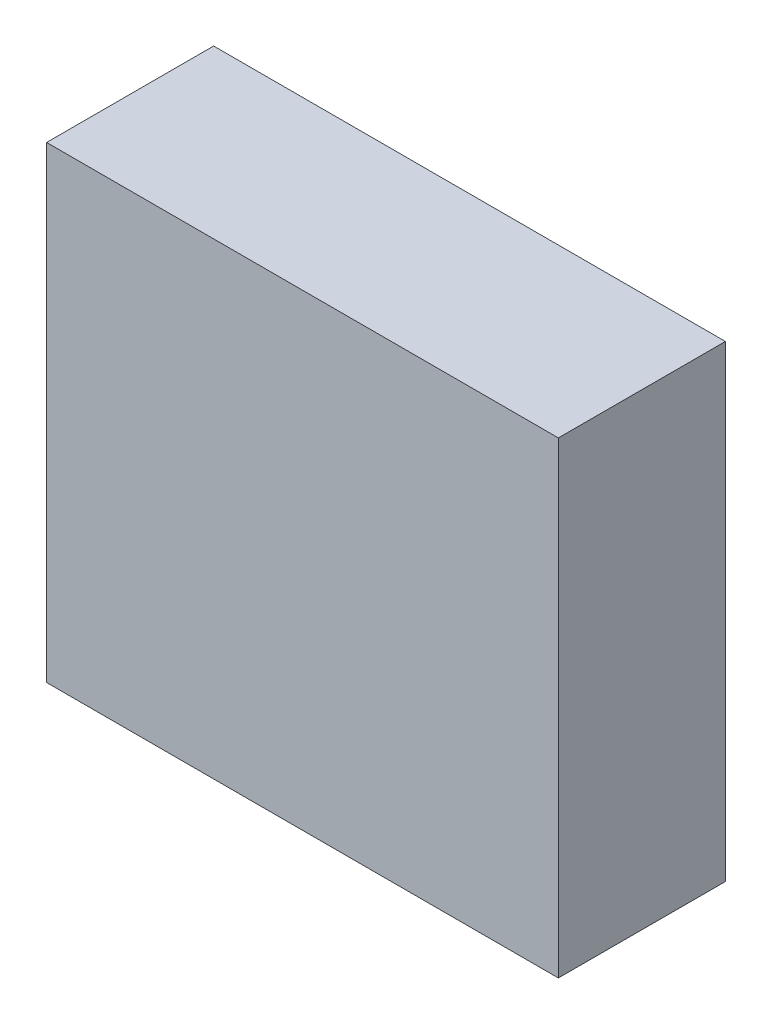
SolidWorks part; units mm, degrees
ref_plane "Front Plane" through (0, 0, 0) normal (0, 0, 1) x (1, 0, 0)
ref_plane "Top Plane" through (0, 0, 0) normal (0, 1, 0) x (1, 0, 0)
ref_plane "Right Plane" through (0, 0, 0) normal (1, 0, 0) x (0, 0, -1)
sketch "Sketch1" plane through (0, 0, 0) normal (0, 0, 1) x (1, 0, 0)
  line L0 (-1.6, 1.4) -> (1.4635, 1.4)
  line L1 (1.4635, 1.4) -> (1.4635, -1.4)
  line L2 (1.4635, -1.4) -> (-1.6, -1.4)
  line L3 (-1.6, -1.4) -> (-1.6, 1.4)
extrude "Component_Outline" add sketch "Sketch1" along normal blind 1 separate body
sketch3d "3DSketch1"
  line L0 (0, 0, 0) -> (1, 0, 0)
  line L1 (0, 0, 0) -> (0, 1, 0)
  line L2 (0, 0, 0) -> (0, 0, 1)
  point P0 (0, 0, 0)
